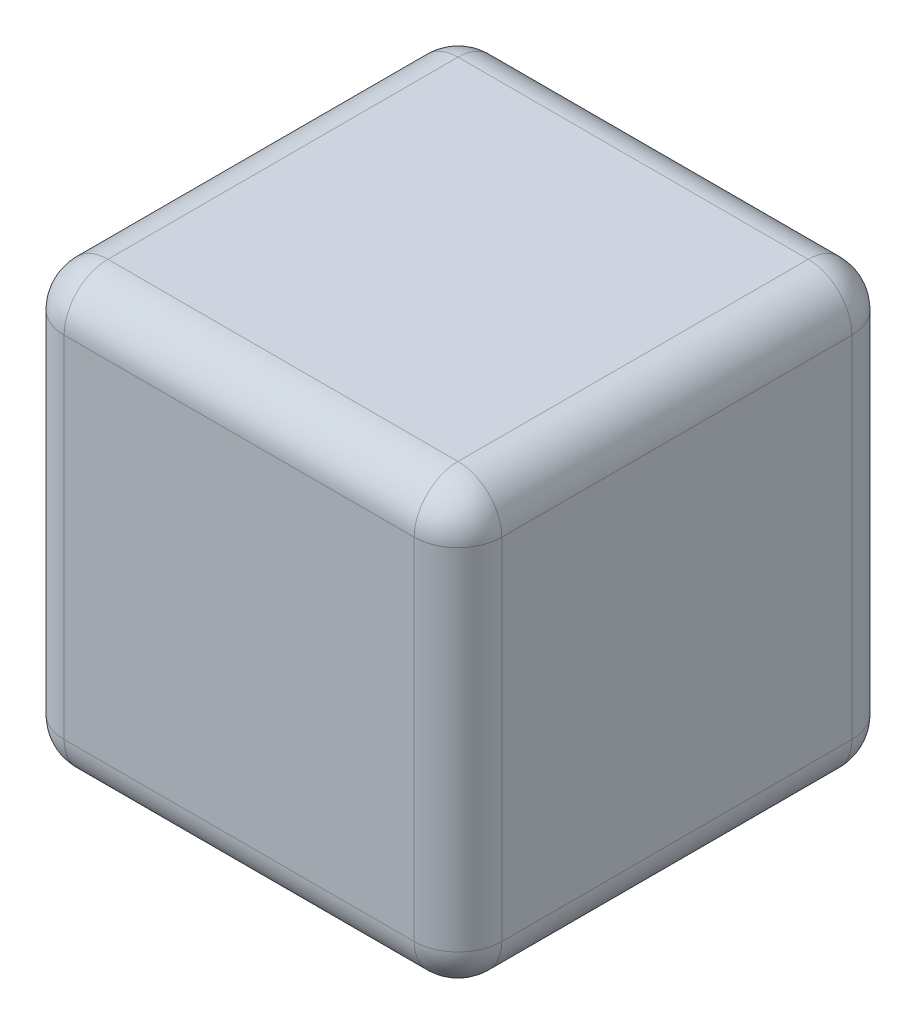
SolidWorks part; units mm, degrees
material "Chrome Stainless Steel"
ref_plane "Front Plane" through (0, 0, 0) normal (0, 0, 1) x (1, 0, 0)
ref_plane "Top Plane" through (0, 0, 0) normal (0, 1, 0) x (1, 0, 0)
ref_plane "Right Plane" through (0, 0, 0) normal (1, 0, 0) x (0, 0, -1)
sketch "Sketch1" plane through (0, 0, 0) normal (0, 1, 0) x (1, 0, 0)
  line L1 (-2.5, 2.5) -> (2.5, 2.5)
  line L2 (-2.5, 2.5) -> (-2.5, -2.5)
  line L3 (-2.5, -2.5) -> (2.5, -2.5)
  line L4 (2.5, 2.5) -> (2.5, -2.5)
  line L5 (-2.5, 2.5) -> (2.5, -2.5) construction
  line L6 (-2.5, -2.5) -> (2.5, 2.5) construction
  point P0 (0, 0)
  dimension "D1" = 5
  dimension "D2" = 5
extrude "Boss-Extrude1" add sketch "Sketch1" along normal blind 5
fillet "Fillet1" radius 0.5 12 edges at (2.5, 2.5, -2.5) (-2.5, 2.5, -2.5) (0, 0, -2.5) (-2.5, 0, 0) (-2.5, 2.5, 2.5) (-2.5, 5, 0) (0, 5, -2.5) (2.5, 0, 0) (0, 0, 2.5) (2.5, 2.5, 2.5) (2.5, 5, 0) (0, 5, 2.5)
